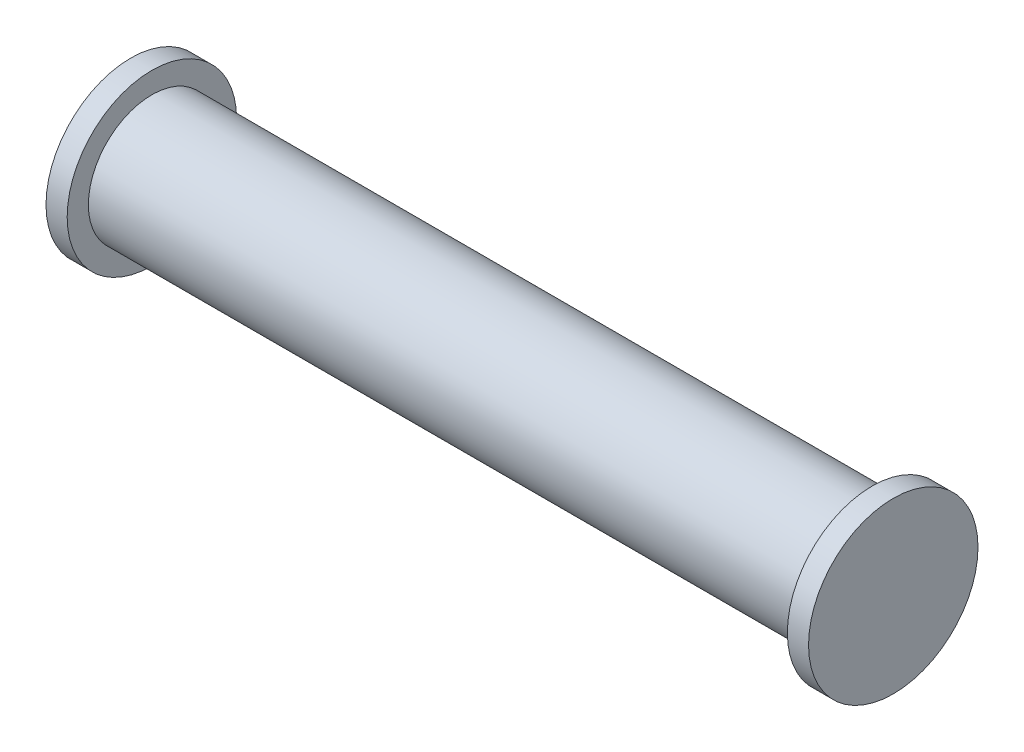
SolidWorks part; units mm, degrees
ref_plane "Front Plane" through (0, 0, 0) normal (0, 0, 1) x (1, 0, 0)
ref_plane "Top Plane" through (0, 0, 0) normal (0, 1, 0) x (1, 0, 0)
ref_plane "Right Plane" through (0, 0, 0) normal (1, 0, 0) x (0, 0, -1)
sketch "Sketch1" plane through (0, 0, 0) normal (1, 0, 0) x (0, 0, -1)
  circle A0 centre (0, 0) radius 3.81
  dimension "D1" = 7.62
extrude "Boss-Extrude1" add sketch "Sketch1" along normal blind 43.18
sketch "Sketch2" plane through (43.18, 0, 0) normal (1, 0, 0) x (0, 0, -1)
  circle A0 centre (0, 0) radius 5.08
  dimension "D1" = 10.16
extrude "Boss-Extrude2" add sketch "Sketch2" along normal blind 1.27
sketch "Sketch3" plane through (0, 0, 0) normal (-1, 0, 0) x (0, 0, 1)
  circle A0 centre (0, 0) radius 5.08
  dimension "D1" = 10.16
extrude "Boss-Extrude3" add sketch "Sketch3" along normal blind 1.27
